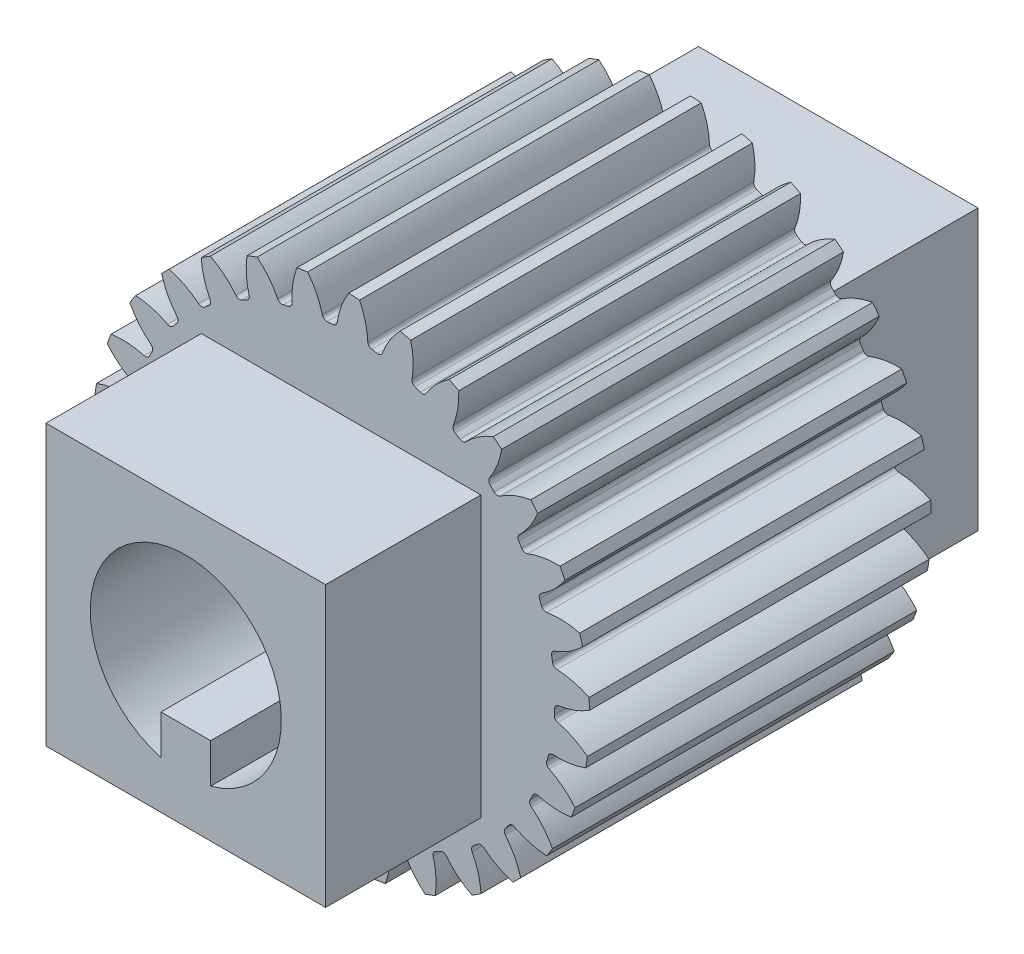
SolidWorks part; units mm, degrees
ref_plane "Alzado" through (0, 0, 0) normal (0, 0, 1) x (1, 0, 0)
ref_plane "Planta" through (0, 0, 0) normal (0, 1, 0) x (1, 0, 0)
ref_plane "Vista lateral" through (0, 0, 0) normal (1, 0, 0) x (0, 0, -1)
sketch "Croquis1" plane through (0, 0, 0) normal (0, 0, 1) x (1, 0, 0)
  circle A0 centre (0, 0) radius 16
  dimension "D1" = 32
extrude "Saliente-Extruir1" add sketch "Croquis1" along normal blind 22
sketch "Croquis3" plane through (0, 0, 22) normal (0, 0, 1) x (1, 0, 0)
  arc A0 (0.4881, 15.9926) -> (-2.1576, 15.8539) centre (0, 0) ccw
  arc A2 (-0.5393, 13.7394) -> (-0.9002, 13.7205) centre (0, 0) ccw
  arc A3 (0.4881, 15.9926) -> (-0.2543, 13.9953) centre (4.8209, 13.2453) ccw
  arc A4 (-2.1576, 15.8539) -> (-1.2104, 13.9452) centre (-6.1793, 12.6687) cw
  arc A5 (-0.2543, 13.9953) -> (-0.5393, 13.7394) centre (-0.5511, 14.0392) cw
  arc A6 (-1.2104, 13.9452) -> (-0.9002, 13.7205) centre (-0.9198, 14.0199) ccw
  dimension "D1" = 32
  dimension "D2" = 0.3
  dimension "D3" = 27.5
extrude "Cortar-Extruir2" cut sketch "Croquis3" against normal blind 22
pattern_circular "MatrizC2" count 30 every 12 about axis through (0, 0, 0) along (0, 0, 1) of "Cortar-Extruir2"
ref_plane "Plano1" through (0, 0, 11) normal (0, 0, -1) x (-1, 0, 0)
sketch "Croquis5" plane through (0, 0, 11) normal (0, 0, -1) x (-1, 0, 0)
  line L1 (-9, -9) -> (9, -9)
  line L2 (-9, -9) -> (-9, 9)
  line L3 (-9, 9) -> (9, 9)
  line L4 (9, -9) -> (9, 9)
  line L5 (-9, -9) -> (9, 9) construction
  line L6 (-9, 9) -> (9, -9) construction
  circle A0 centre (0, 0) radius 6.25 construction
  dimension "D1" = 12.5
  dimension "D2" = 18
  dimension "D3" = 18
extrude "Saliente-Extruir2" add sketch "Croquis5" along normal mid plane 42
sketch "Croquis8" plane through (0, 0, -10) normal (0, 0, -1) x (-1, 0, 0)
  circle A0 centre (0, 0) radius 6.15
  dimension "D1" = 12.3
extrude "Cortar-Extruir3" cut sketch "Croquis8" against normal through all
sketch "Croquis9" plane through (0, 0, -10) normal (0, 0, -1) x (-1, 0, 0)
  line L0 (0, 0) -> (0, -6.15) construction
  line L1 (-1.6, -8.9) -> (1.6, -8.9)
  line L2 (-1.6, -8.9) -> (-1.6, -3.4)
  line L3 (-1.6, -3.4) -> (1.6, -3.4)
  line L4 (1.6, -8.9) -> (1.6, -3.4)
  line L5 (-1.6, -8.9) -> (1.6, -3.4) construction
  line L6 (-1.6, -3.4) -> (1.6, -8.9) construction
  circle A0 centre (0, 0) radius 6.15 construction
  circle A1 centre (0, 0) radius 6.15
  point P0 (0, -6.15)
  circle M3 centre (0, 0) radius 6.15
  dimension "D1" = 5.5
  dimension "D2" = 3.2
extrude "Saliente-Extruir6" add sketch "Croquis9" against normal up to surface (42 mm away) contours L4 L3 L2 M3 | L1 L4 L2 M3
